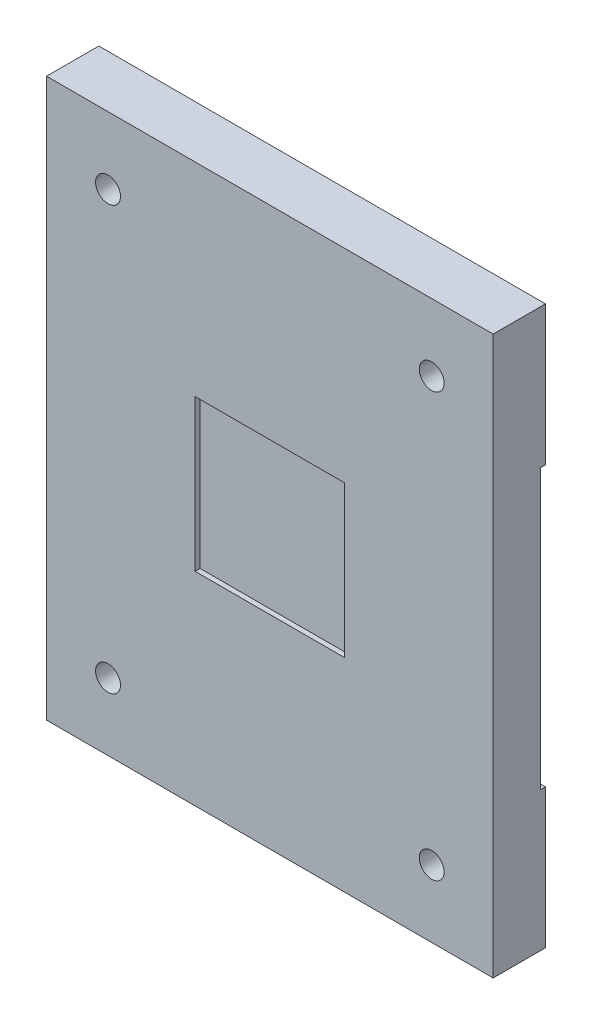
SolidWorks part; units mm, degrees
ref_plane "前视基准面" through (0, 0, 0) normal (0, 0, 1) x (1, 0, 0)
ref_plane "上视基准面" through (0, 0, 0) normal (0, 1, 0) x (1, 0, 0)
ref_plane "右视基准面" through (0, 0, 0) normal (1, 0, 0) x (0, 0, -1)
sketch "草图1" plane through (0, 0, 0) normal (0, 0, 1) x (1, 0, 0)
  line L1 (-27.5, 39.2042) -> (62.2, 39.2042)
  line L2 (62.2, 39.2042) -> (62.2, -72.7958)
  line L3 (62.2, -72.7958) -> (-27.5, -72.7958)
  line L4 (-27.5, 39.2042) -> (-27.5, -72.7958)
  line L5 (-27.5, -65.2723) -> (-27.5, 0.7231) construction
  dimension "D1" = 112
  dimension "D2" = 89.7
extrude "凸台-拉伸1" add sketch "草图1" along normal up to vertex (10.5 mm away)
sketch "草图2" plane through (0, 0, 10.5) normal (0, 0, 1) x (1, 0, 0)
  line L12 (17.35, -1.5958) -> (32.35, -1.5958)
  line L13 (32.35, -1.5958) -> (32.35, -31.9958)
  line L14 (32.35, -31.9958) -> (2.35, -31.9958)
  line L15 (2.35, -31.9958) -> (2.35, -1.5958)
  line L16 (17.35, -1.5958) -> (2.35, -1.5958)
  dimension "D2" = 30.4
  dimension "D3" = 15
  dimension "D4" = 30
extrude "切除-拉伸1" cut sketch "草图2" against normal blind 1
sketch "草图3" plane through (0, 0, 0) normal (0, 0, -1) x (-1, 0, 0)
  line L1 (-62.2, -72.7958) -> (-62.2, 39.2042) construction
  line L3 (-62.2, -16.7958) -> (-62.2, -44.7958)
  line L4 (-62.2, -16.7958) -> (-62.2, 11.2042)
  line L5 (-62.2, 11.2042) -> (27.5, 11.2042)
  line L6 (27.5, 39.2042) -> (27.5, -72.7958) construction
  line L7 (27.5, 11.2042) -> (27.5, -44.7958)
  line L8 (27.5, -44.7958) -> (-62.2, -44.7958)
  dimension "D1" = 28
  dimension "D2" = 28
extrude "切除-拉伸2" cut sketch "草图3" against normal blind 1
sketch "草图4" plane through (0, 0, 0) normal (0, 0, -1) x (-1, 0, 0)
  line L0 (-62.2, -16.7958) -> (27.5, -16.7958) construction
  line L3 (-62.2, 11.2042) -> (-62.2, -44.7958) construction
  line L12 (27.5, -44.7958) -> (27.5, 11.2042) construction
  line L13 (-17.35, 25.7042) -> (-17.35, 18.7488) construction
  line L14 (-49.85, -59.2958) -> (15.15, -59.2958) construction
  line L15 (-49.85, -59.2958) -> (-49.85, 25.7042) construction
  line L16 (-49.85, 25.7042) -> (15.15, 25.7042) construction
  line L17 (15.15, -59.2958) -> (15.15, 25.7042) construction
  line L18 (-49.85, -59.2958) -> (15.15, 25.7042) construction
  line L19 (-49.85, 25.7042) -> (15.15, -59.2958) construction
  circle A0 centre (-49.85, 25.7042) radius 5
  circle A1 centre (15.15, 25.7042) radius 5
  circle A2 centre (15.15, -59.2958) radius 5
  circle A3 centre (-49.85, -59.2958) radius 5
  point P6 (-15.5986, -17.808)
  point P7 (-15.5986, -17.808)
  point P12 (-17.35, -16.7958)
  dimension "D3" = 10
  dimension "D1" = 65
  dimension "D2" = 85
extrude "切除-拉伸3" cut sketch "草图4" against normal blind 4
sketch "草图15" plane through (0, 0, 4) normal (0, 0, -1) x (-1, 0, 0)
  circle A0 centre (-49.85, 25.7042) radius 2.5
  circle A1 centre (15.15, 25.7042) radius 2.5
  circle A2 centre (-49.85, -59.2958) radius 2.5
  circle A3 centre (15.15, -59.2958) radius 2.5
  dimension "D1" = 5
  dimension "D2" = 5
  dimension "D3" = 5
  dimension "D4" = 5
extrude "切除-拉伸4" cut sketch "草图15" against normal blind 10
